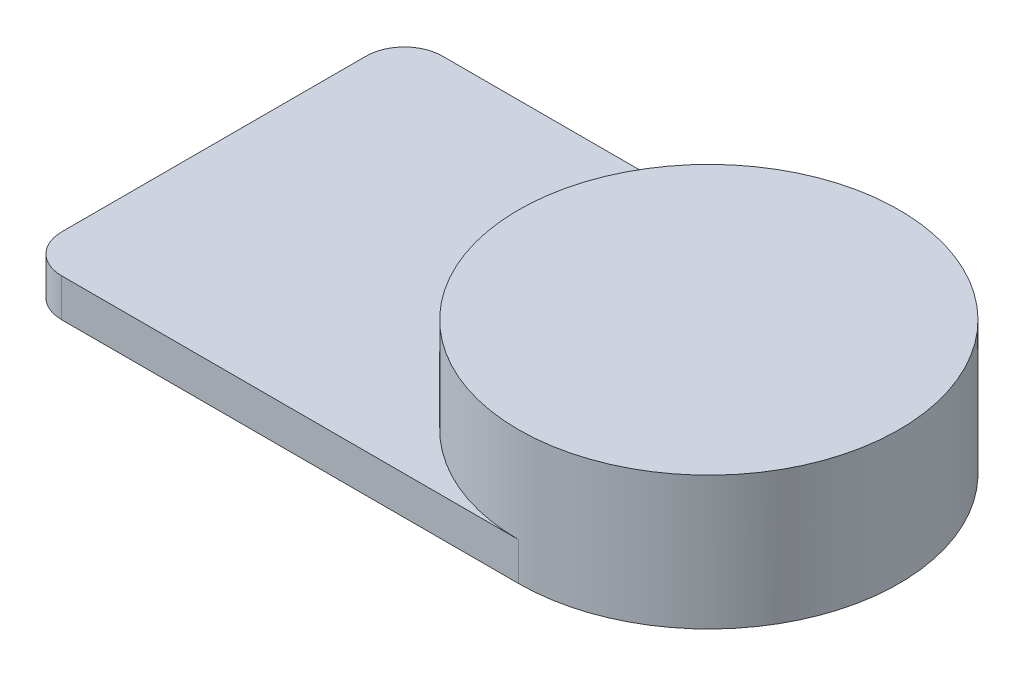
SolidWorks part; units mm, degrees
ref_plane "Front Plane" through (0, 0, 0) normal (0, 0, 1) x (1, 0, 0)
ref_plane "Top Plane" through (0, 0, 0) normal (0, 1, 0) x (1, 0, 0)
ref_plane "Right Plane" through (0, 0, 0) normal (1, 0, 0) x (0, 0, -1)
sketch "Sketch1" plane through (0, 0, 0) normal (0, 1, 0) x (1, 0, 0)
  line L1 (0, 50) -> (-130, 50)
  line L2 (0, 50) -> (0, -50)
  line L3 (0, -50) -> (-130, -50)
  line L4 (-130, 50) -> (-130, -50)
  circle A0 centre (0, 0) radius 50
  dimension "D1" = 100
  dimension "D2" = 130
  dimension "D3" = 100
extrude "Boss-Extrude8" add sketch "Sketch1" along normal blind 10 contours L2 A0 | A0 L1 L4 L3 | L2 A0
sketch "Sketch8" plane through (0, 10, 0) normal (0, 1, 0) x (1, 0, 0)
  circle A0 centre (0, 0) radius 50
extrude "Boss-Extrude9" add sketch "Sketch8" along normal blind 25
sketch "Sketch9" plane through (0, 0, 0) normal (0, -1, 0) x (1, 0, 0)
  line L0 (-130, 50) -> (0, -50) construction
  line L2 (-115, 40) -> (-15, 40)
  line L3 (-115, 40) -> (-115, -40)
  line L4 (-115, -40) -> (-15, -40)
  line L5 (-15, 40) -> (-15, -40)
  line L6 (-115, 40) -> (-15, -40) construction
  line L7 (-115, -40) -> (-15, 40) construction
  circle A0 centre (-15, 40) radius 5
  circle A1 centre (-15, -40) radius 5
  circle A2 centre (-115, -40) radius 5
  circle A3 centre (-115, 40) radius 5
  point P4 (-65, 0)
  dimension "D3" = 10
  dimension "D1" = 80
  dimension "D2" = 100
extrude "Cut-Extrude8" cut sketch "Sketch9" against normal blind 5 contours A3 | A0 | A1 | A2
fillet "Fillet1" radius 10 2 edges at (-130, 5, -50) (-130, 5, 50)
